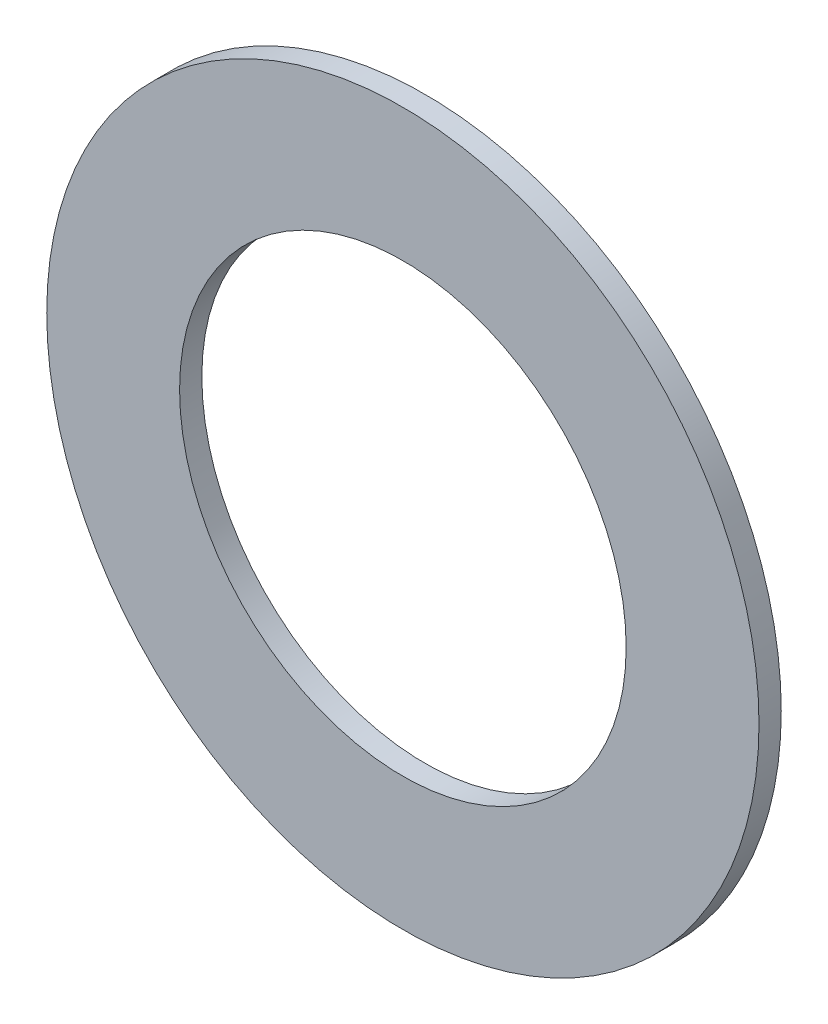
SolidWorks part; units mm, degrees
material "Commercial Bronze, UNS C22000 (90-10 Bronze)"
ref_plane "Front Plane" through (0, 0, 0) normal (0, 0, 1) x (1, 0, 0)
ref_plane "Top Plane" through (0, 0, 0) normal (0, 1, 0) x (1, 0, 0)
ref_plane "Right Plane" through (0, 0, 0) normal (1, 0, 0) x (0, 0, -1)
sketch "Sketch1" plane through (0, 0, 0) normal (0, 0, 1) x (1, 0, 0)
  circle A0 centre (0, 0) radius 25.4
  circle A1 centre (0, 0) radius 15.9258
  dimension "D1" = 50.8
  dimension "ID" = 31.8516
extrude "Extrude1" add sketch "Sketch1" along normal mid plane 1.5875
sketch "Sketch2" plane through (0, 0, 0) normal (1, 0, 0) x (0, 0, -1)
  line L0 (-0.7937, -15.9258) -> (0.7937, -15.9258) construction
  line L3 (0.7937, 15.9258) -> (-0.7937, 15.9258) construction
  line L5 (-0.7937, -15.9258) -> (0.7937, -15.9258)
  line L6 (0.7937, 15.9258) -> (-0.7937, 15.9258)
sketch "Sketch4" plane through (0, 0, 0.7937) normal (0, 0, 1) x (1, 0, 0)
  line L0 (0, 0) -> (-11.2612, 11.2612)
  line L1 (0, -1.7463) -> (0, 1.7463) construction
  circle A0 centre (0, 0) radius 15.9258 construction
  dimension "D1" = 45
